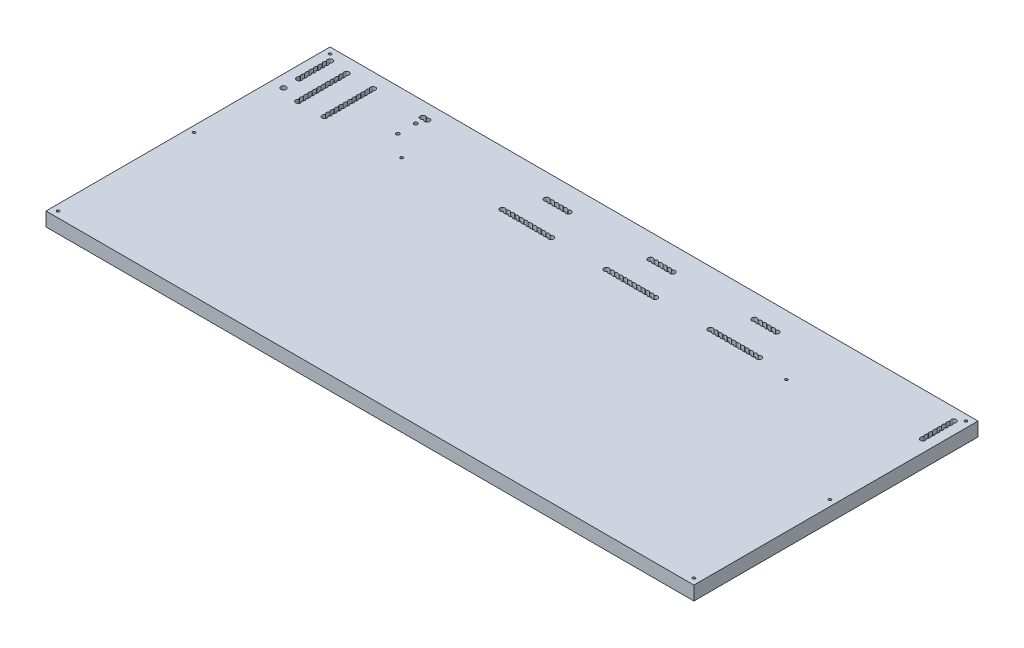
SolidWorks part; units mm, degrees
ref_plane "前视基准面" through (0, 0, 0) normal (0, 0, 1) x (1, 0, 0)
ref_plane "上视基准面" through (0, 0, 0) normal (0, 1, 0) x (1, 0, 0)
ref_plane "右视基准面" through (0, 0, 0) normal (1, 0, 0) x (0, 0, -1)
sketch "草图1" plane through (0, 0, 0) normal (0, 1, 0) x (1, 0, 0)
  line L1 (-187, -82) -> (187, -82)
  line L2 (-187, -82) -> (-187, 82)
  line L3 (-187, 82) -> (187, 82)
  line L4 (187, -82) -> (187, 82)
  line L5 (-187, -82) -> (187, 82) construction
  line L6 (-187, 82) -> (187, -82) construction
  circle A0 centre (-180, 75) radius 1.5
  circle A1 centre (-180, 72.46) radius 1.5
  circle A2 centre (-180, 69.92) radius 1.5
  circle A3 centre (-180, 67.38) radius 1.5
  circle A4 centre (-180, 64.84) radius 1.5
  circle A5 centre (-180, 62.3) radius 1.5
  circle A6 centre (-180, 59.76) radius 1.5
  circle A7 centre (-180, 57.22) radius 1.5
  circle A8 centre (-180, 48.1) radius 1.5
  circle A9 centre (-183.5, 78.5) radius 0.7835
  circle A10 centre (183.5, 78.5) radius 0.7835
  circle A11 centre (183.5, 0) radius 0.7835
  circle A12 centre (183.5, -78.5) radius 0.7835
  circle A13 centre (-183.5, 0) radius 0.7835
  circle A14 centre (-183.5, -78.5) radius 0.7835
  circle A15 centre (-111, 47.3) radius 0.7835
  circle A16 centre (111, 47.4) radius 0.7835
  circle A17 centre (180, 75) radius 1.5
  circle A18 centre (180, 72.46) radius 1.5
  circle A19 centre (180, 69.92) radius 1.5
  circle A20 centre (180, 67.38) radius 1.5
  circle A21 centre (180, 64.84) radius 1.5
  circle A22 centre (180, 62.3) radius 1.5
  circle A23 centre (180, 59.76) radius 1.5
  circle A24 centre (180, 57.22) radius 1.5
  circle A25 centre (-168.998, 73.523) radius 1.5
  circle A26 centre (-153.758, 73.523) radius 1.5
  circle A27 centre (-153.758, 70.983) radius 1.5
  circle A28 centre (-153.758, 68.443) radius 1.5
  circle A29 centre (-153.758, 65.903) radius 1.5
  circle A30 centre (-153.758, 63.363) radius 1.5
  circle A31 centre (-153.758, 60.823) radius 1.5
  circle A32 centre (-153.758, 58.283) radius 1.5
  circle A33 centre (-153.758, 55.743) radius 1.5
  circle A34 centre (-153.758, 53.203) radius 1.5
  circle A35 centre (-153.758, 50.663) radius 1.5
  circle A36 centre (-153.758, 48.123) radius 1.5
  circle A37 centre (-153.758, 45.583) radius 1.5
  circle A38 centre (-168.998, 70.983) radius 1.5
  circle A39 centre (-168.998, 68.443) radius 1.5
  circle A40 centre (-168.998, 65.903) radius 1.5
  circle A41 centre (-168.998, 63.363) radius 1.5
  circle A42 centre (-168.998, 60.823) radius 1.5
  circle A43 centre (-168.998, 58.283) radius 1.5
  circle A44 centre (-168.998, 55.743) radius 1.5
  circle A45 centre (-168.998, 53.203) radius 1.5
  circle A46 centre (-168.998, 50.663) radius 1.5
  circle A47 centre (-168.998, 48.123) radius 1.5
  circle A48 centre (-168.998, 45.583) radius 1.5
  circle A49 centre (-124.97, 73.5) radius 1.5
  circle A50 centre (-122.43, 73.5) radius 1.5
  circle A51 centre (-124.018, 68.45) radius 1
  circle A52 centre (-124.018, 58.15) radius 1
  circle A53 centre (-48.348, 68.316) radius 1.5
  circle A54 centre (-45.808, 68.316) radius 1.5
  circle A55 centre (-43.268, 68.316) radius 1.5
  circle A56 centre (-40.728, 68.316) radius 1.5
  circle A57 centre (-38.188, 68.316) radius 1.5
  circle A58 centre (-35.648, 68.316) radius 1.5
  circle A59 centre (11.652, 68.316) radius 1.5
  circle A60 centre (14.192, 68.316) radius 1.5
  circle A61 centre (16.732, 68.316) radius 1.5
  circle A62 centre (19.272, 68.316) radius 1.5
  circle A63 centre (21.812, 68.316) radius 1.5
  circle A64 centre (24.352, 68.316) radius 1.5
  circle A65 centre (71.652, 68.316) radius 1.5
  circle A66 centre (74.192, 68.316) radius 1.5
  circle A67 centre (76.732, 68.316) radius 1.5
  circle A68 centre (79.272, 68.316) radius 1.5
  circle A69 centre (81.812, 68.316) radius 1.5
  circle A70 centre (84.352, 68.316) radius 1.5
  circle A71 centre (-55.968, 50.536) radius 1.5
  circle A72 centre (-53.428, 50.536) radius 1.5
  circle A73 centre (-50.888, 50.536) radius 1.5
  circle A74 centre (-48.348, 50.536) radius 1.5
  circle A75 centre (-45.808, 50.536) radius 1.5
  circle A76 centre (-43.268, 50.536) radius 1.5
  circle A77 centre (-40.728, 50.536) radius 1.5
  circle A78 centre (-38.188, 50.536) radius 1.5
  circle A79 centre (-35.648, 50.536) radius 1.5
  circle A80 centre (-33.108, 50.536) radius 1.5
  circle A81 centre (-30.568, 50.536) radius 1.5
  circle A82 centre (-28.028, 50.536) radius 1.5
  circle A83 centre (4.032, 50.536) radius 1.5
  circle A84 centre (6.572, 50.536) radius 1.5
  circle A85 centre (9.112, 50.536) radius 1.5
  circle A86 centre (11.652, 50.536) radius 1.5
  circle A87 centre (14.192, 50.536) radius 1.5
  circle A88 centre (16.732, 50.536) radius 1.5
  circle A89 centre (19.272, 50.536) radius 1.5
  circle A90 centre (21.812, 50.536) radius 1.5
  circle A91 centre (24.352, 50.536) radius 1.5
  circle A92 centre (26.892, 50.536) radius 1.5
  circle A93 centre (29.432, 50.536) radius 1.5
  circle A94 centre (31.972, 50.536) radius 1.5
  circle A95 centre (64.032, 50.536) radius 1.5
  circle A96 centre (66.572, 50.536) radius 1.5
  circle A97 centre (69.112, 50.536) radius 1.5
  circle A98 centre (71.652, 50.536) radius 1.5
  circle A99 centre (74.192, 50.536) radius 1.5
  circle A100 centre (76.732, 50.536) radius 1.5
  circle A101 centre (79.272, 50.536) radius 1.5
  circle A102 centre (81.812, 50.536) radius 1.5
  circle A103 centre (84.352, 50.536) radius 1.5
  circle A104 centre (86.892, 50.536) radius 1.5
  circle A105 centre (89.432, 50.536) radius 1.5
  circle A106 centre (91.972, 50.536) radius 1.5
  point P0 (0, 0)
  point P5 (-180, 75)
  dimension "D5" = 3
  dimension "D8" = 7
  dimension "D10" = 3
  dimension "D11" = 3.5
  dimension "D13" = 1.567
  dimension "D16" = 1.567
  dimension "D21" = 1.567
  dimension "D26" = 3.5
  dimension "D28" = 3
  dimension "D36" = 3
  dimension "D41" = 2
  dimension "D46" = 3
  dimension "D53" = 3
  dimension "D1" = 374
  dimension "D2" = 164
  dimension "D3" = 7
  dimension "D4" = 7
  dimension "D6" = 8
  dimension "D7" = 2.54
  dimension "D9" = 33.9
  dimension "D12" = 3.5
  dimension "D17" = 76
  dimension "D18" = 34.7
  dimension "D19" = 78.5
  dimension "D20" = 367
  dimension "D22" = 298
  dimension "D23" = 34.6
  dimension "D25" = 7
  dimension "D27" = 7
  dimension "D29" = 18.002
  dimension "D30" = 8.477
  dimension "D33" = 2.54
  dimension "D34" = 11.017
  dimension "D35" = 15.24
  dimension "D37" = 8.5
  dimension "D38" = 62.03
  dimension "D40" = 2.54
  dimension "D42" = 13.55
  dimension "D43" = 62.982
  dimension "D45" = 10.3
  dimension "D47" = 13.684
  dimension "D48" = 138.652
  dimension "D50" = 2.54
  dimension "D52" = 60
  dimension "D54" = 31.464
  dimension "D55" = 131.032
  dimension "D57" = 2.54
  dimension "D59" = 60
  dimension "D14" = 2
  dimension "D15" = 3
  dimension "D24" = 2
  dimension "D31" = 2
  dimension "D32" = 12
  dimension "D39" = 2
  dimension "D44" = 2
  dimension "D49" = 6
  dimension "D51" = 3
  dimension "D56" = 12
  dimension "D58" = 3
extrude "凸台-拉伸1" add sketch "草图1" along normal blind 8 contours L1 L4 L3 L2 A8 A7 A6 A5 A4 A3 A2 A1 A0
cosmetic thread "装饰螺纹线1" parameters "D2"=2
cosmetic thread "装饰螺纹线2" parameters "D2"=2
cosmetic thread "装饰螺纹线3" parameters "D2"=2
cosmetic thread "装饰螺纹线4" parameters "D2"=2
cosmetic thread "装饰螺纹线5" parameters "D2"=2
cosmetic thread "装饰螺纹线6" parameters "D2"=2
cosmetic thread "装饰螺纹线7" parameters "D2"=2
cosmetic thread "装饰螺纹线8" parameters "D2"=2
